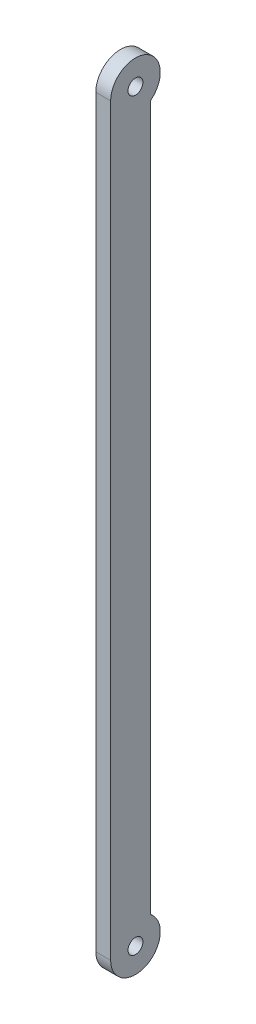
SolidWorks part; units mm, degrees
ref_plane "Alzado" through (0, 0, 0) normal (0, 0, 1) x (1, 0, 0)
ref_plane "Planta" through (0, 0, 0) normal (0, 1, 0) x (1, 0, 0)
ref_plane "Vista lateral" through (0, 0, 0) normal (1, 0, 0) x (0, 0, -1)
sketch "Croquis1" plane through (0, 0, 0) normal (1, 0, 0) x (0, 0, -1)
  line L0 (0, 0) -> (0, 150) construction
  line L1 (-5, 150) -> (-5, 0)
  line L2 (3, 146) -> (3, 4)
  arc A0 (-5, 0) -> (3, 4) centre (0, 0) ccw
  arc A1 (3, 146) -> (-5, 150) centre (0, 150) ccw
  circle A4 centre (0, 150) radius 1.5
  circle A5 centre (0, 0) radius 1.5
  dimension "D1" = 5
  dimension "D2" = 150
  dimension "D3" = 3
  dimension "D4" = 3
  dimension "D5" = 8
extrude "Saliente-Extruir2" add sketch "Croquis1" along normal blind 3
